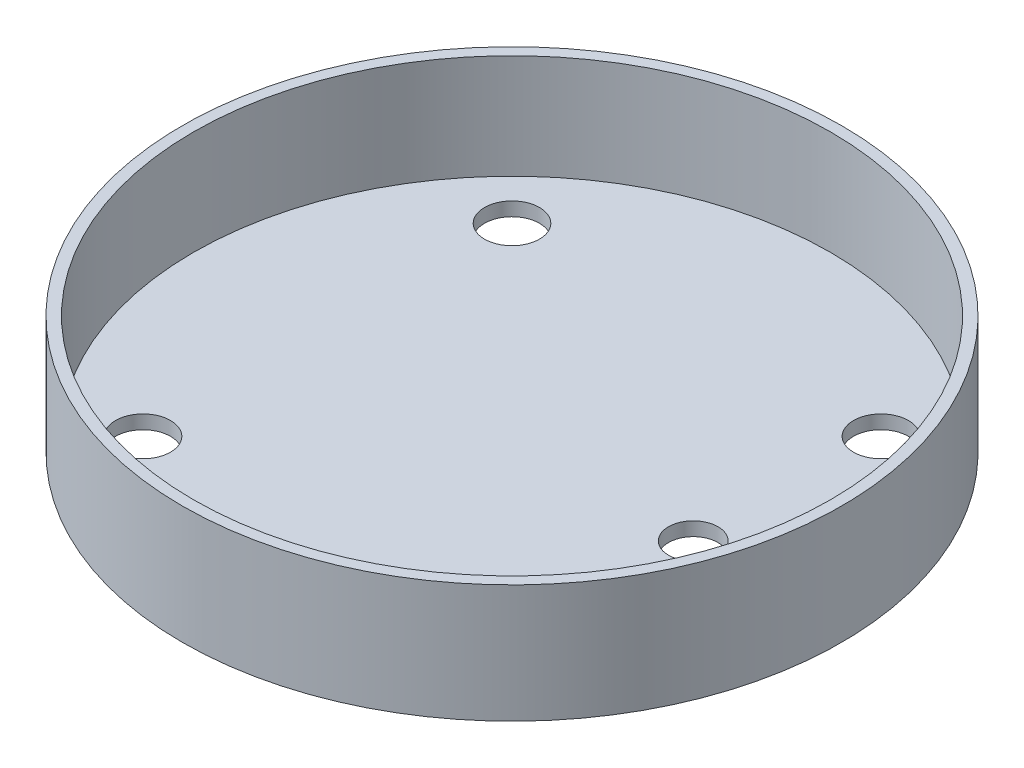
SolidWorks part; units mm, degrees
ref_plane "Front Plane" through (0, 0, 0) normal (0, 0, 1) x (1, 0, 0)
ref_plane "Top Plane" through (0, 0, 0) normal (0, 1, 0) x (1, 0, 0)
ref_plane "Right Plane" through (0, 0, 0) normal (1, 0, 0) x (0, 0, -1)
sketch "Sketch1" plane through (0, 0, 0) normal (0, 1, 0) x (1, 0, 0)
  circle A0 centre (0, 0) radius 60
  dimension "D1" = 120
extrude "Boss-Extrude1" add sketch "Sketch1" along normal blind 2.5
sketch "Sketch2" plane through (0, 2.5, 0) normal (0, 1, 0) x (1, 0, 0)
  circle A1 centre (0, 0) radius 60
  circle A2 centre (0, 0) radius 60
  circle A4 centre (0, 0) radius 58
  circle A5 centre (0, 0) radius 58
  dimension "D1" = 0
  dimension "D2" = 2
extrude "Boss-Extrude2" add sketch "Sketch2" along normal blind 19
sketch "Sketch3" plane through (0, 2.5, 0) normal (0, 1, 0) x (1, 0, 0)
  line L0 (0, 0) -> (33, 0) construction
  line L1 (0, 0) -> (33.5876, 33.5876) construction
  circle A0 centre (33, 0) radius 4.5
  circle A1 centre (33.5876, 33.5876) radius 5
  circle A2 centre (33.5876, -33.5876) radius 5
  circle A3 centre (-33.5876, -33.5876) radius 5
  circle A4 centre (-33.5876, 33.5876) radius 5
  dimension "D4" = 10
  dimension "D5" = 9
  dimension "D1" = 45
  dimension "D2" = 33
  dimension "D3" = 47.5
  dimension "D6" = 4
extrude "Cut-Extrude1" cut sketch "Sketch3" against normal through all
